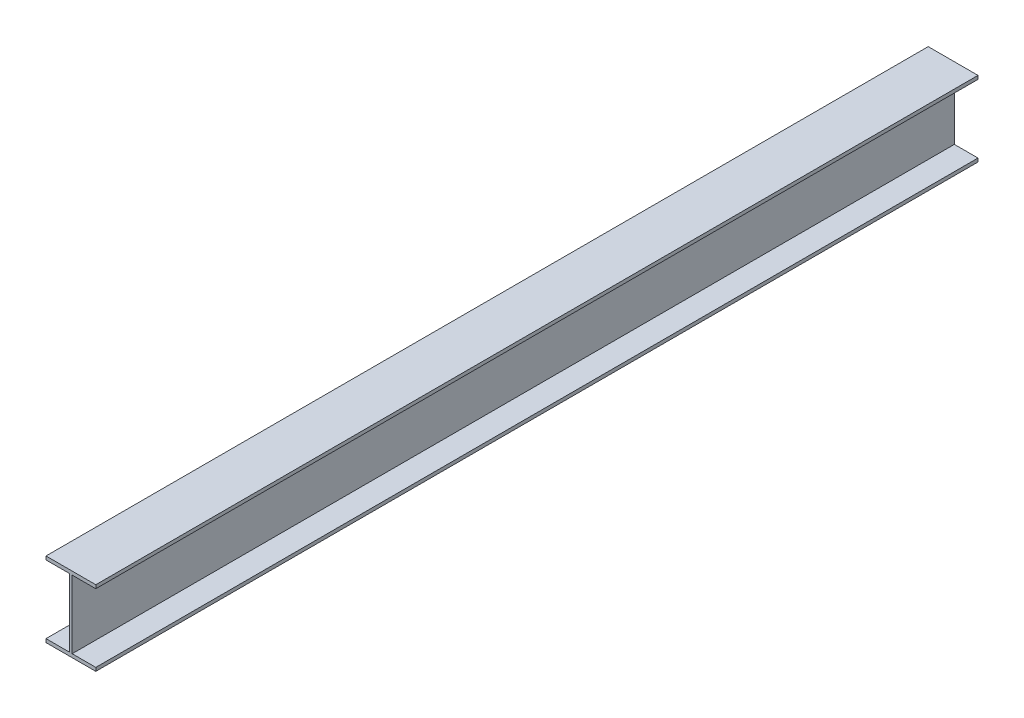
SolidWorks part; units mm, degrees
material "ASTM A992 Steel"
ref_plane "Front" through (0, 0, 0) normal (0, 0, 1) x (1, 0, 0)
ref_plane "Top" through (0, 0, 0) normal (0, 1, 0) x (1, 0, 0)
ref_plane "Right" through (0, 0, 0) normal (1, 0, 0) x (0, 0, -1)
sketch "Sketch1" plane through (0, 0, 0) normal (0, 0, 1) x (1, 0, 0)
  line L0 (0, -0.0002) -> (101.6, -0.0002)
  line L1 (101.6, -0.0002) -> (101.6, -7.1122)
  line L2 (101.6, -7.1122) -> (53.408, -7.1122)
  line L3 (53.408, -7.1122) -> (53.408, -146.0502)
  line L4 (53.408, -146.0502) -> (101.6, -146.0502)
  line L5 (101.6, -146.0502) -> (101.6, -153.1622)
  line L6 (101.6, -153.1622) -> (0, -153.1622)
  line L7 (0, -153.1622) -> (0, -146.0502)
  line L8 (0, -146.0502) -> (47.566, -146.0502)
  line L9 (47.566, -146.0502) -> (47.566, -7.1122)
  line L10 (47.566, -7.1122) -> (0, -7.1122)
  line L11 (0, -7.1122) -> (0, -0.0002)
  line L12 (50.8, -0.0002) -> (50.8, -153.1622) construction
  dimension "D1" = 5.842
  dimension "D2" = 7.112
  dimension "D3" = 7.112
  dimension "D4" = 7.112
  dimension "D5" = 153.162
  dimension "D6" = 50.8
  dimension "D7" = 50.8
  dimension "D8" = 47.566
extrude "Boss-Extrude1" add sketch "Sketch1" along normal blind 1800
sketch "Sketch2" plane through (0, -153.1622, 0) normal (0, -1, 0) x (1, 0, 0)
  line L0 (0, 1800) -> (0, 0) construction
  line L1 (0, 1050) -> (250, 1050)
  line L2 (0, 1050) -> (0, 750)
  line L3 (0, 750) -> (250, 750)
  line L4 (250, 1050) -> (250, 750)
  point P6 (0, 900)
  point P7 (0, 900)
  dimension "D1" = 150
  dimension "D2" = 250
split line "Split Line1"
